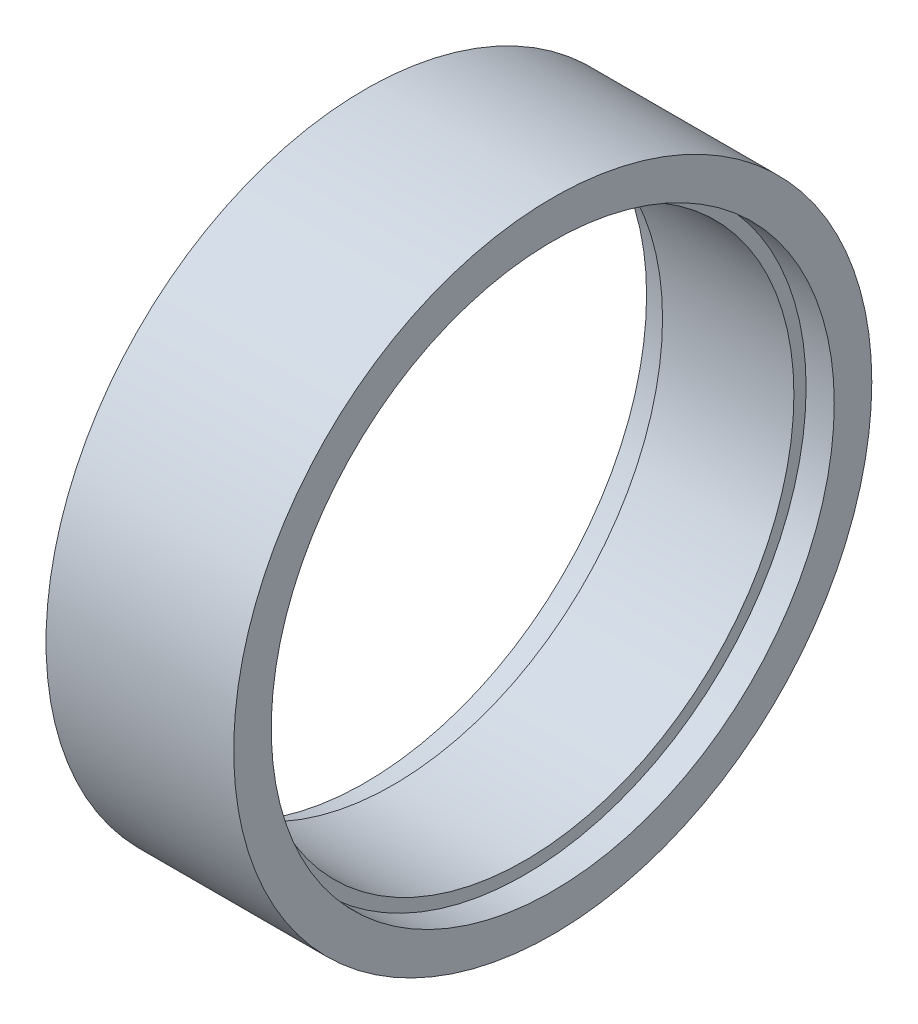
SolidWorks part; units mm, degrees
material "POLYURETHANE (11671)"
ref_plane "Front Plane" through (0, 0, 0) normal (0, 0, 1) x (1, 0, 0)
ref_plane "Top Plane" through (0, 0, 0) normal (0, 1, 0) x (1, 0, 0)
ref_plane "Right Plane" through (0, 0, 0) normal (1, 0, 0) x (0, 0, -1)
sketch "Sketch2" plane through (0, 0, 0) normal (1, 0, 0) x (0, 0, -1)
  circle A0 centre (0, 0) radius 15
  circle A1 centre (0, 0) radius 14.35
extrude "Boss-Extrude1" add sketch "Sketch2" along normal blind 7
ref_plane "Plane1" through (7, 0, 0) normal (1, 0, 0) x (0, 0, -1)
sketch "Sketch3" plane through (7, 0, 0) normal (1, 0, 0) x (0, 0, -1)
  circle A0 centre (0, 0) radius 15
  circle A1 centre (0, 0) radius 17
extrude "Boss-Extrude2" add sketch "Sketch3" along normal blind 1.5 and the other way blind 8.5 separate body
ref_plane "Plane2" through (8.5, 0, 0) normal (1, 0, 0) x (0, 0, -1)
